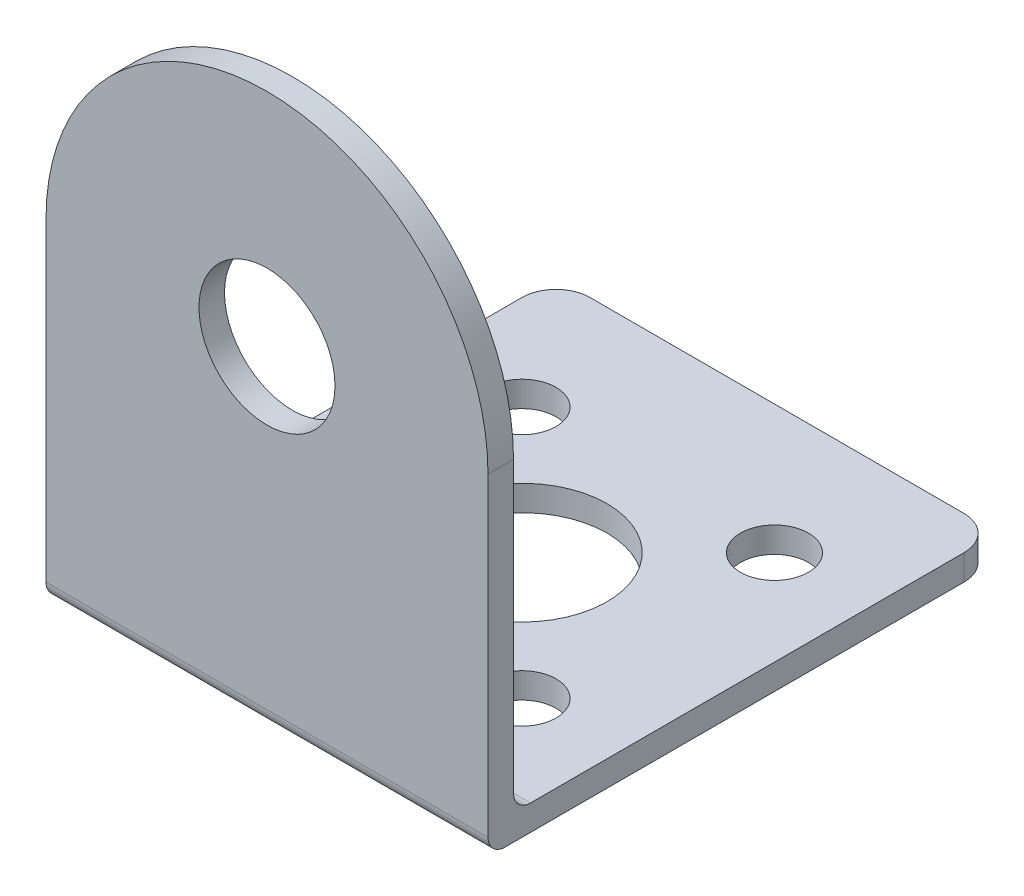
SolidWorks part; units mm, degrees
ref_plane "Front Plane" through (0, 0, 0) normal (0, 0, 1) x (1, 0, 0)
ref_plane "Top Plane" through (0, 0, 0) normal (0, 1, 0) x (1, 0, 0)
ref_plane "Right Plane" through (0, 0, 0) normal (1, 0, 0) x (0, 0, -1)
sketch "Sketch1" plane through (0, 0, 0) normal (0, 1, 0) x (1, 0, 0)
  line L1 (-13, -15) -> (13, -15)
  line L2 (-13, -15) -> (-13, 15)
  line L3 (-13, 15) -> (13, 15)
  line L4 (13, -15) -> (13, 15)
  line L5 (-13, -15) -> (13, 15) construction
  line L6 (-13, 15) -> (13, -15) construction
  point P0 (0, 0)
  dimension "D1" = 26
  dimension "D2" = 30
extrude "Boss-Extrude1" add sketch "Sketch1" along normal blind 1.5
sketch "Sketch3" plane through (0, 0, 15) normal (0, 0, 1) x (1, 0, 0)
  line L0 (-13, 1.5) -> (-13, 19.5)
  line L1 (13, 19.5) -> (13, 1.5)
  line L2 (13, 1.5) -> (-13, 1.5)
  arc A0 (-13, 19.5) -> (13, 19.5) centre (0, 19.5) cw
  point P5 (13, 30.7744)
  dimension "D1" = 18
extrude "Boss-Extrude2" add sketch "Sketch3" against normal blind 1.5
sketch "Sketch4" plane through (0, 0, 15) normal (0, 0, 1) x (1, 0, 0)
  circle A0 centre (0, 19.5) radius 4
  dimension "D1" = 8
extrude "Cut-Extrude1" cut sketch "Sketch4" against normal through all
fillet "Fillet1" radius 1 2 edges at (0, 0, 15) (0, 1.5, 13.5)
fillet "Fillet2" radius 2 2 edges at (-13, 0.75, -15) (13, 0.75, -15)
sketch "Sketch5" plane through (0, 0, 0) normal (0, -1, 0) x (1, 0, 0)
  line L0 (10.3837, 10.3837) -> (-10.3837, -10.3837) construction
  line L2 (0, 0) -> (0, 5) construction
  line L3 (-8.9599, 8.9599) -> (8.9599, -8.9599) construction
  circle A0 centre (0, 0) radius 5
  circle A1 centre (7.4246, 7.4246) radius 2
  circle A2 centre (-7.4246, -7.4246) radius 2
  circle A5 centre (-7.4246, 7.4246) radius 2
  circle A6 centre (7.4246, -7.4246) radius 2
  point P6 (0, -5)
  point P7 (0, 0)
  point P14 (0, 0)
  point P19 (0, 0)
  point P20 (0, 0)
  point P21 (0, 0)
  point P22 (0, 0)
  dimension "D1" = 10
  dimension "D5" = 4
  dimension "D2" = 45
  dimension "D3" = 90
  dimension "D4" = 21
  dimension "D6" = 21
extrude "Cut-Extrude2" cut sketch "Sketch5" against normal through all
